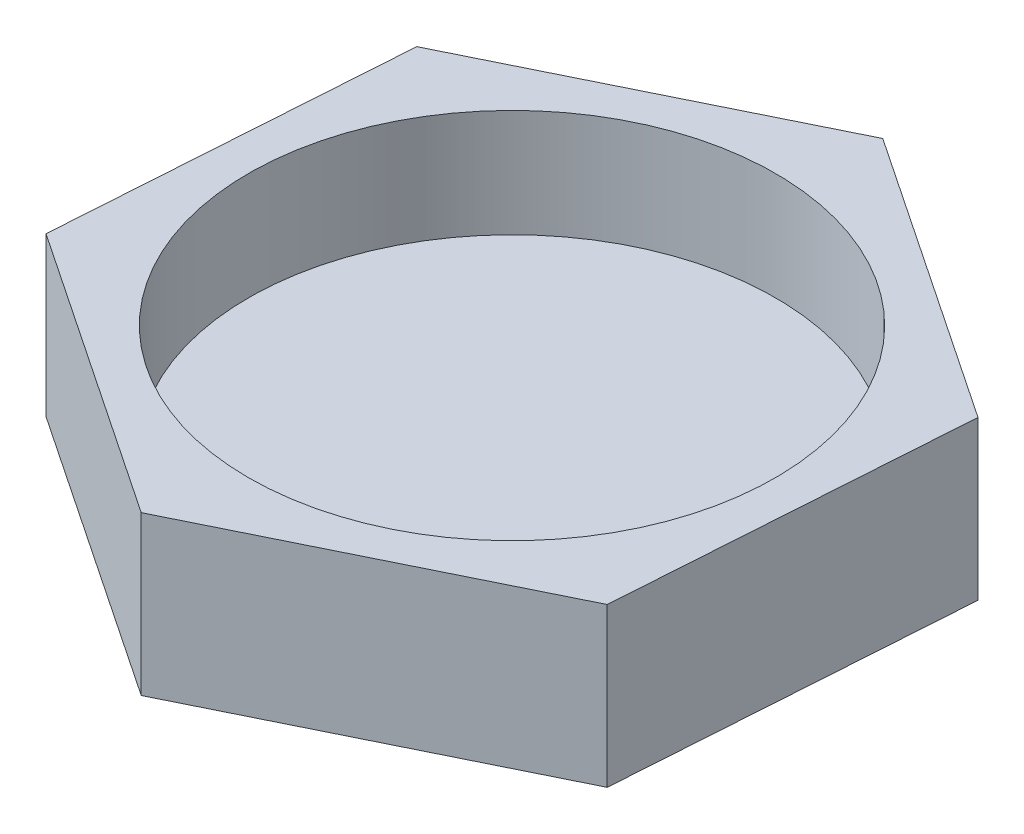
SolidWorks part; units mm, degrees
ref_plane "Front Plane" through (0, 0, 0) normal (0, 0, 1) x (1, 0, 0)
ref_plane "Top Plane" through (0, 0, 0) normal (0, 1, 0) x (1, 0, 0)
ref_plane "Right Plane" through (0, 0, 0) normal (1, 0, 0) x (0, 0, -1)
sketch "Sketch1" plane through (0, 0, 0) normal (0, 1, 0) x (1, 0, 0)
  line L1 (14.4933, -9.7202) -> (15.6646, 7.6914)
  line L2 (15.6646, 7.6914) -> (1.1713, 17.4116)
  line L3 (1.1713, 17.4116) -> (-14.4933, 9.7202)
  line L4 (-14.4933, 9.7202) -> (-15.6646, -7.6914)
  line L5 (-15.6646, -7.6914) -> (-1.1713, -17.4116)
  line L6 (-1.1713, -17.4116) -> (14.4933, -9.7202)
  circle A0 centre (0, 0) radius 15.113 construction
  dimension "D1" = 30.226
extrude "Boss-Extrude1" add sketch "Sketch1" along normal blind 7.9375
sketch "Sketch2" plane through (0, 7.9375, 0) normal (0, 1, 0) x (1, 0, 0)
  circle A0 centre (0, 0) radius 13.208
  dimension "D1" = 26.416
extrude "Cut-Extrude1" cut sketch "Sketch2" against normal offset from surface (5.3975 mm away) 2.54 up to face at (0, 0, 0)
